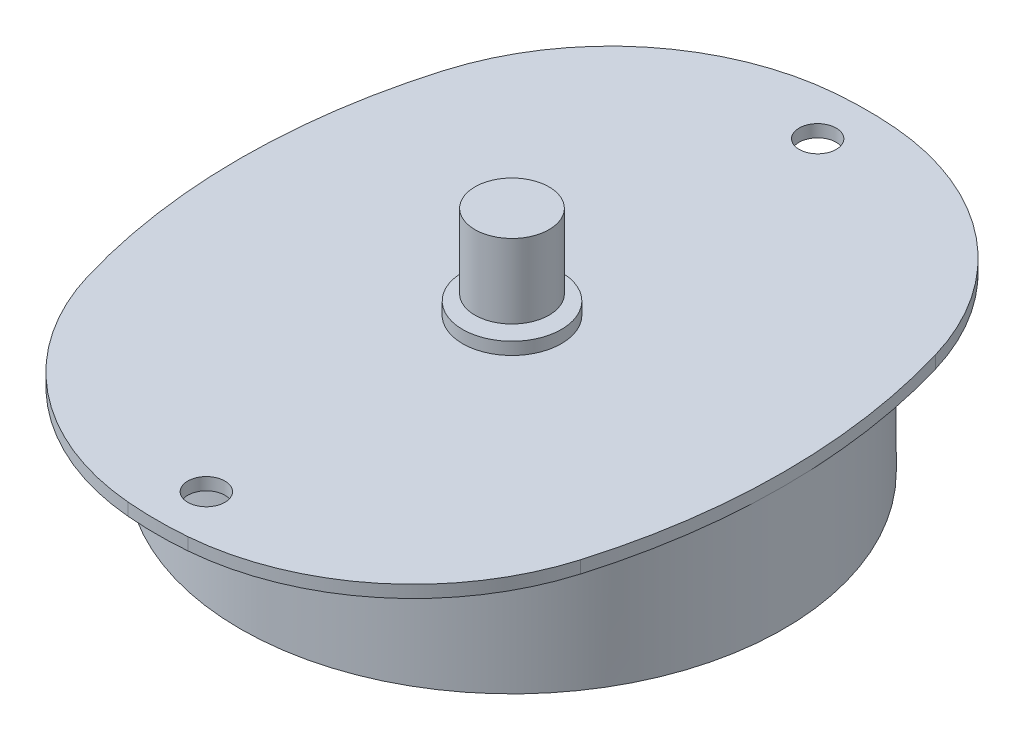
SolidWorks part; units mm, degrees
material "AISI 304"
ref_plane "Front Plane" through (0, 0, 0) normal (0, 0, 1) x (1, 0, 0)
ref_plane "Top Plane" through (0, 0, 0) normal (0, 1, 0) x (1, 0, 0)
ref_plane "Right Plane" through (0, 0, 0) normal (1, 0, 0) x (0, 0, -1)
sketch "Sketch1" plane through (0, 0, 0) normal (0, 1, 0) x (1, 0, 0)
  circle A0 centre (0, 0) radius 22
  dimension "D1" = 44
extrude "Boss-Extrude1" add sketch "Sketch1" along normal blind 10
sketch "Sketch2" plane through (0, 10, 0) normal (0, 1, 0) x (1, 0, 0)
  circle A0 centre (0, 0) radius 28.75
  dimension "D1" = 57.5
extrude "Boss-Extrude2" add sketch "Sketch2" along normal blind 1
sketch "Sketch3" plane through (0, 11, 0) normal (0, 1, 0) x (1, 0, 0)
  circle A0 centre (0, -24.75) radius 1.5
  circle A1 centre (0, 24.75) radius 1.5
  circle A2 centre (0, 0) radius 28.75 construction
  dimension "D3" = 3
  dimension "D4" = 3
  dimension "D1" = 24.75
  dimension "D2" = 24.75
extrude "Cut-Extrude1" cut sketch "Sketch3" against normal blind 1
sketch "Sketch4" plane through (0, 10, 0) normal (0, -1, 0) x (1, 0, 0)
  circle A0 centre (28.75, 0) radius 50.75
  circle A1 centre (0, 0) radius 28.75 construction
  circle A2 centre (-28.75, 0) radius 50.75
  circle M4 centre (0, 0) radius 28.75
extrude "Cut-Extrude2" cut sketch "Sketch4" against normal blind 1 contours A0 M4 | A2 M4
fillet "Fillet1" radius 20 4 edges at (-16.0424, 10.5, 23.858) (-16.0424, 10.5, -23.858) (16.0424, 10.5, -23.858) (16.0424, 10.5, 23.858)
sketch "Sketch5" plane through (0, 11, 0) normal (0, 1, 0) x (1, 0, 0)
  circle A0 centre (0, 0) radius 4
  dimension "D1" = 8
extrude "Boss-Extrude3" add sketch "Sketch5" along normal blind 1
sketch "Sketch6" plane through (0, 12, 0) normal (0, 1, 0) x (1, 0, 0)
  circle A0 centre (0, 0) radius 1
  dimension "D1" = 2
extrude "Boss-Extrude4" add sketch "Sketch6" along normal blind 0.5
sketch "Sketch7" plane through (0, 12.5, 0) normal (0, 1, 0) x (1, 0, 0)
  circle A0 centre (0, 0) radius 3
  dimension "D1" = 6
extrude "Boss-Extrude5" add sketch "Sketch7" along normal blind 6
equation "\"D1@Sketch2\"=49.5+8"
equation "\"D1@Sketch3\"=\"D1@Sketch2\"/2-4"
equation "\"D2@Sketch3\"=\"D1@Sketch3\""
